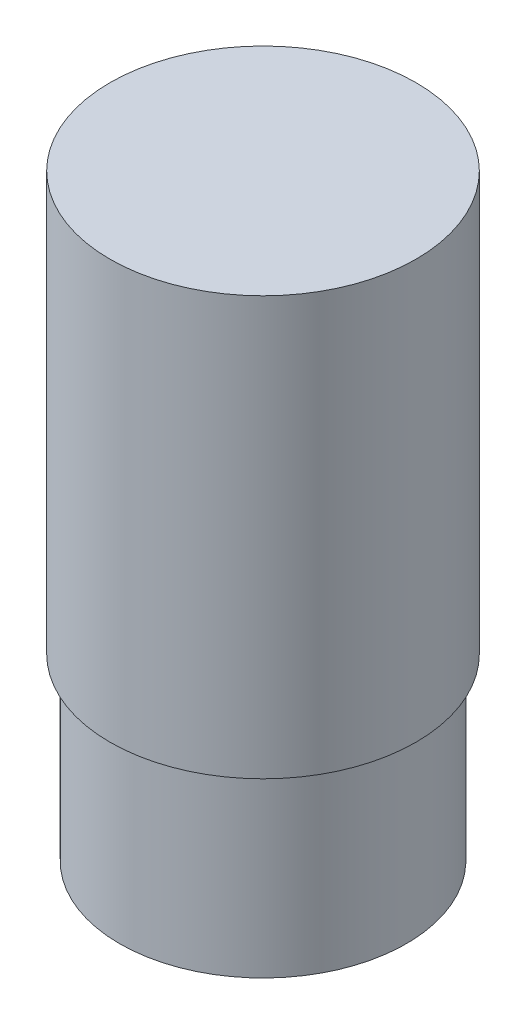
SolidWorks part; units mm, degrees
material "Brass"
ref_plane "Front Plane" through (0, 0, 0) normal (0, 0, 1) x (1, 0, 0)
ref_plane "Top Plane" through (0, 0, 0) normal (0, 1, 0) x (1, 0, 0)
ref_plane "Right Plane" through (0, 0, 0) normal (1, 0, 0) x (0, 0, -1)
sketch "Sketch1" plane through (0, 0, 0) normal (0, 1, 0) x (1, 0, 0)
  circle A0 centre (0, 0) radius 4.064
  dimension "D1" = 8.128
extrude "Boss-Extrude1" add sketch "Sketch1" along normal blind 15.875
sketch "Sketch2" plane through (0, 0, 0) normal (0, -1, 0) x (1, 0, 0)
  circle A0 centre (0, 0) radius 3.81
  circle A1 centre (0, 0) radius 4.064 construction
  circle A2 centre (0, 0) radius 4.064
  dimension "D1" = 7.62
extrude "Cut-Extrude1" cut sketch "Sketch2" against normal blind 4.7625
